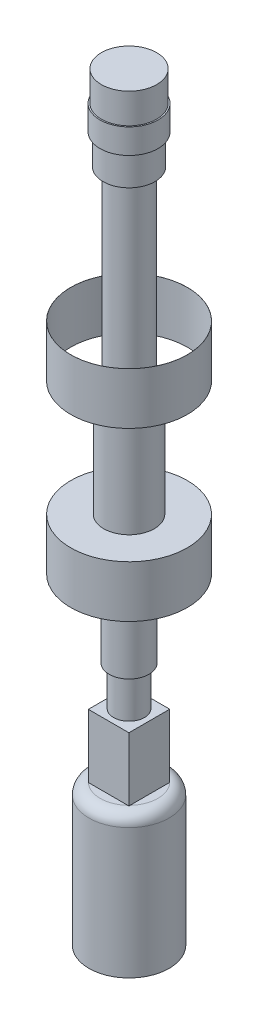
SolidWorks part; units mm, degrees
ref_plane "前视基准面" through (0, 0, 0) normal (0, 0, 1) x (1, 0, 0)
ref_plane "上视基准面" through (0, 0, 0) normal (0, 1, 0) x (1, 0, 0)
ref_plane "右视基准面" through (0, 0, 0) normal (1, 0, 0) x (0, 0, -1)
sketch "草图6" plane through (0, 0, 0) normal (0, 1, 0) x (1, 0, 0)
  circle A0 centre (36.9159, 31.0812) radius 17.7322
extrude "凸台-拉伸4" add sketch "草图6" along normal blind 10
sketch "草图7" plane through (0, 10, 0) normal (0, 1, 0) x (1, 0, 0)
  circle A0 centre (36.9159, 31.0812) radius 35.4211
extrude "凸台-拉伸5" add sketch "草图7" along normal blind 95
sketch "草图8" plane through (0, 105, 0) normal (0, 1, 0) x (1, 0, 0)
  circle A0 centre (36.9159, 31.0812) radius 35.4211
extrude "凸台-拉伸6" add sketch "草图8" along normal blind 30
fillet "圆角1" radius 10 1 edges at (36.9159, 135, 4.3399)
sketch "草图9" plane through (0, 135, 0) normal (0, 1, 0) x (1, 0, 0)
  line L1 (19.4889, 12.5736) -> (55.3117, 12.5736)
  line L2 (19.4889, 12.5736) -> (19.4889, 48.6262)
  line L3 (19.4889, 48.6262) -> (55.3117, 48.6262)
  line L4 (55.3117, 12.5736) -> (55.3117, 48.6262)
  circle A0 centre (36.9159, 31.0812) radius 25.4211 construction
extrude "凸台-拉伸7" add sketch "草图9" along normal blind 56
sketch "草图10" plane through (0, 191, 0) normal (0, 1, 0) x (1, 0, 0)
  circle A0 centre (36.9159, 31.0812) radius 13.6624
extrude "凸台-拉伸8" add sketch "草图10" along normal blind 35
sketch "草图11" plane through (0, 226, 0) normal (0, 1, 0) x (1, 0, 0)
  circle A0 centre (36.9159, 31.0812) radius 17.545
extrude "凸台-拉伸9" add sketch "草图11" along normal blind 48
sketch "草图12" plane through (0, 274, 0) normal (0, 1, 0) x (1, 0, 0)
  circle A0 centre (36.9159, 31.0812) radius 12.5
extrude "凸台-拉伸10" add sketch "草图12" along normal blind 20
sketch "草图13" plane through (0, 294, 0) normal (0, 1, 0) x (1, 0, 0)
  circle A0 centre (36.9159, 31.0812) radius 49
  circle A1 centre (36.9159, 31.0812) radius 36
sketch "草图14" plane through (0, 274, 0) normal (0, 1, 0) x (1, 0, 0)
  circle A0 centre (36.9159, 31.0812) radius 20
extrude "凸台-拉伸12" add sketch "草图14" along normal blind 20
extrude "凸台-拉伸13" add sketch "草图13" along normal blind 20 separate body
sketch "草图15" plane through (0, 294, 0) normal (0, 1, 0) x (1, 0, 0)
  circle A0 centre (36.9159, 31.0812) radius 51.5
extrude "凸台-拉伸14" add sketch "草图15" along normal blind 45.7
sketch "草图16" plane through (0, 339.7, 0) normal (0, 1, 0) x (1, 0, 0)
  circle A0 centre (36.9159, 31.0812) radius 38
  circle A1 centre (36.9159, 31.0812) radius 22.325
  circle A2 centre (36.9159, 31.0812) radius 19.8
  point P5 (0, 0)
extrude "凸台-拉伸17" add sketch "草图16" along normal blind 102 contours A1
sketch "草图17" plane through (0, 441.7, 0) normal (0, 1, 0) x (1, 0, 0)
  circle A0 centre (36.9159, 31.0812) radius 51.51
  circle A1 centre (36.9159, 31.0812) radius 51.55
extrude "凸台-拉伸19" add sketch "草图17" along normal blind 45.7 separate body
sketch "草图18" plane through (0, 441.7, 0) normal (0, 1, 0) x (1, 0, 0)
  circle A0 centre (36.9159, 31.0812) radius 17.03
extrude "凸台-拉伸20" add sketch "草图18" along normal blind 163.76
sketch "草图19" plane through (0, 605.46, 0) normal (0, 1, 0) x (1, 0, 0)
  circle A0 centre (36.9159, 31.0812) radius 22.89
extrude "凸台-拉伸21" add sketch "草图19" along normal blind 26.64
sketch "草图20" plane through (0, 632.1, 0) normal (0, 1, 0) x (1, 0, 0)
  circle A0 centre (36.9159, 31.0812) radius 25.615
extrude "凸台-拉伸22" add sketch "草图20" along normal blind 21.88
sketch "草图21" plane through (0, 653.98, 0) normal (0, 1, 0) x (1, 0, 0)
  circle A0 centre (36.9159, 31.0812) radius 24.44
extrude "凸台-拉伸23" add sketch "草图21" along normal blind 26.5
